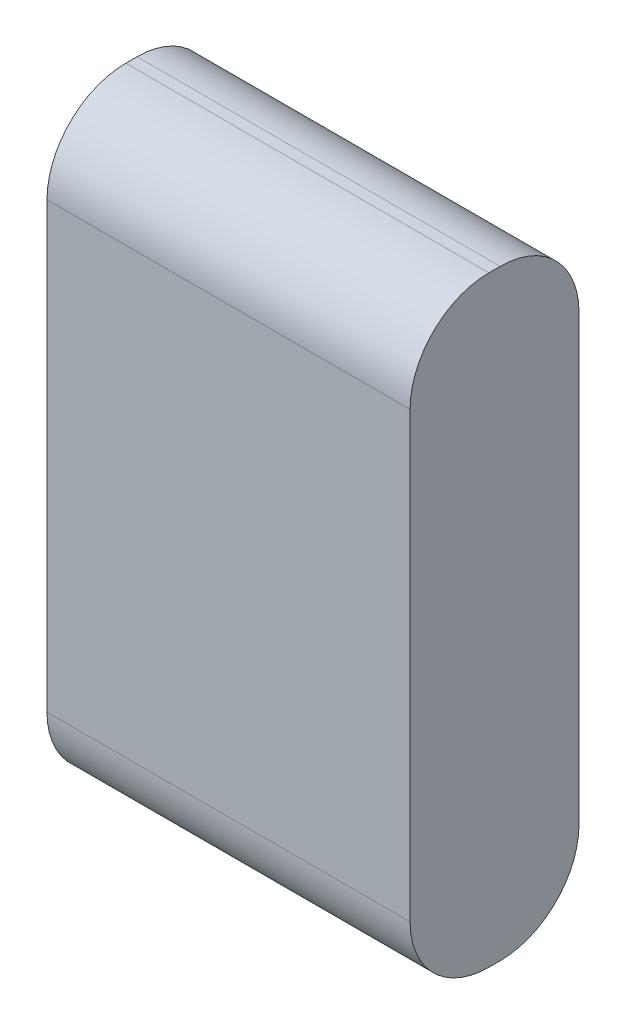
SolidWorks part; units mm, degrees
ref_plane "Front Plane" through (0, 0, 0) normal (0, 0, 1) x (1, 0, 0)
ref_plane "Top Plane" through (0, 0, 0) normal (0, 1, 0) x (1, 0, 0)
ref_plane "Right Plane" through (0, 0, 0) normal (1, 0, 0) x (0, 0, -1)
sketch "Sketch2" plane through (0, 0, 0) normal (0, 1, 0) x (1, 0, 0)
  line L1 (0, 0) -> (80.6, 0)
  line L2 (0, 0) -> (0, 37.5)
  line L3 (0, 37.5) -> (80.6, 37.5)
  line L4 (80.6, 0) -> (80.6, 37.5)
  dimension "D1" = 80.6
  dimension "D2" = 37.5
extrude "Boss-Extrude1" add sketch "Sketch2" along normal blind 133.5
fillet "Fillet1" radius 17.5 4 edges at (40.3, 133.5, 0) (40.3, 133.5, -37.5) (40.3, 0, 0) (40.3, 0, -37.5)
